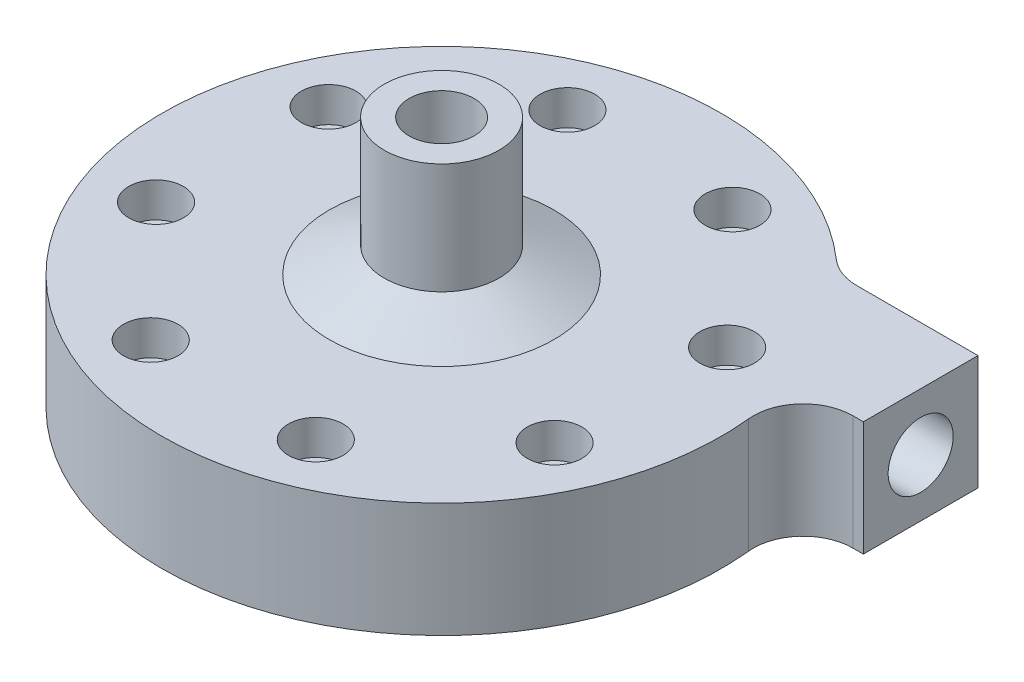
SolidWorks part; units mm, degrees
material "1060 Alloy"
ref_plane "Front" through (0, 0, 0) normal (0, 0, 1) x (1, 0, 0)
ref_plane "Top" through (0, 0, 0) normal (0, 1, 0) x (1, 0, 0)
ref_plane "Right" through (0, 0, 0) normal (1, 0, 0) x (0, 0, -1)
sketch "Sketch1" plane through (0, 0, 0) normal (0, 1, 0) x (1, 0, 0)
  line L0 (0, 0) -> (2.6731, 30.5538) construction
  line L1 (21.117, 30.6705) -> (50.1264, 33.2085) construction
  line L2 (11.6189, 28.3845) -> (50.1264, 28.3845) construction
  line L3 (21.117, 26.0945) -> (50.1264, 23.5565) construction
  line L4 (0, 0) -> (56.1418, -4.9118) construction
  line L5 (21.117, 30.6705) -> (21.117, 28.3845) construction
  line L6 (21.117, 28.3845) -> (21.117, 26.0945) construction
  line L7 (50.1264, 28.3845) -> (50.1264, 33.2085) construction
  line L8 (50.1264, 28.3845) -> (50.1264, 23.5565) construction
  line L9 (68.1264, 28.3845) -> (68.1264, 39.9329)
  line L10 (68.1264, 34.9329) -> (50.1264, 34.9329) construction
  line L11 (68.1264, 34.9329) -> (68.1264, 21.8361) construction
  line L12 (68.1264, 21.8361) -> (50.1264, 21.8361) construction
  line L13 (50.1264, 34.9329) -> (50.1264, 21.8361) construction
  line L14 (68.1264, 39.9329) -> (43.7019, 39.9329)
  line L15 (68.1264, 28.3845) -> (68.1264, 16.8361)
  line L16 (68.1264, 16.8361) -> (66.0032, 16.8361)
  line L17 (21.117, 30.6705) -> (0, 30.6705) construction
  line L18 (21.117, 26.0945) -> (16.117, 26.0945) construction
  arc A0 (37.1159, 42.408) -> (56.0564, 5.8059) centre (0, 0) ccw
  circle A1 centre (0, 0) radius 30.6705 construction
  arc A2 (66.0032, 16.8361) -> (56.0564, 5.8059) centre (66.0032, 6.8361) ccw
  arc A3 (43.7019, 39.9329) -> (37.1159, 42.408) centre (43.7019, 49.9329) cw
  dimension "D1" = 112.7125
  dimension "D2" = 61.341
  dimension "D13" = 10
  dimension "D4" = 2.286
  dimension "D3" = 2.29
  dimension "D5" = 5
  dimension "D6" = 5
  dimension "D7" = 5
  dimension "D8" = 9.652
  dimension "D9" = 13.0969
  dimension "D10" = 18
  dimension "D11" = 5
  dimension "D12" = 5
  dimension "D14" = 5
extrude "main body" add sketch "Sketch1" along normal blind 23.0969
ref_plane "body midsection" through (0, 11.5484, 0) normal (0, 1, 0) x (1, 0, 0)
sketch "Sketch7" plane through (0, 23.0969, 0) normal (0, 1, 0) x (1, 0, 0)
  circle A0 centre (0, 0) radius 25.4
  dimension "D1" = 50.8
extrude "inlet boss" add sketch "Sketch7" along normal blind 50.8
sketch "Sketch3" plane through (0, 11.5484, 0) normal (0, 1, 0) x (1, 0, 0)
  line L0 (21.117, 30.6705) -> (0, 30.6705)
  line L1 (0, 30.6705) -> (0, 28.3845)
  line L2 (50.1264, 28.3845) -> (2.4833, 28.3845)
  line L3 (0, 0) -> (2.6731, 30.5538) construction
  line L4 (0, 28.3845) -> (2.4833, 28.3845)
  line L5 (50.1264, 33.2085) -> (50.1264, 34.9329)
  line L6 (50.1264, 34.9329) -> (68.1264, 34.9329)
  line L7 (68.1264, 34.9329) -> (68.1264, 28.3845)
  line L8 (68.1264, 28.3845) -> (50.1264, 28.3845)
  line L9 (21.117, 30.6705) -> (50.1264, 33.2085)
revolve "expansion cone and outlet" cut sketch "Sketch3" angle 360 about L2
sketch "Sketch2" plane through (0, 0, 0) normal (0, 0, 1) x (1, 0, 0)
  line L0 (-56.3562, 11.5484) -> (56.3562, 11.5484) construction
  line L1 (-56.3562, 23.0969) -> (-56.3562, 0) construction
  line L2 (56.3562, 0) -> (56.3562, 23.0969) construction
  line L3 (0, 0) -> (0, 23.0969) construction
  line L4 (25.4, 23.0969) -> (-25.4, 23.0969) construction
  line L5 (0, 25.0381) -> (0, 13.3702)
  line L6 (0, 13.3702) -> (26.67, 13.3702) construction
  line L7 (5.461, 25.0381) -> (5.6723, 25.4913) construction
  line L8 (26.67, 15.1482) -> (5.461, 15.1482) construction
  line L9 (26.67, 13.3702) -> (26.67, 15.1482) construction
  line L10 (0, 25.5898) -> (0, 50.5898)
  line L11 (26.67, 15.1482) -> (5.461, 25.0381) construction
  line L12 (5.461, 25.0381) -> (0, 25.0381) construction
  line L13 (5.461, 25.0381) -> (5.461, 13.3702) construction
  line L14 (0, 13.3702) -> (0, 11.3702) construction
  line L15 (0, 11.3702) -> (26.67, 11.3702) construction
  line L16 (26.67, 11.3702) -> (26.67, 13.3702) construction
  line L17 (0, 13.3702) -> (0, 10.8702)
  line L18 (0, 11.3702) -> (0, 10.8702) construction
  line L19 (0, 10.8702) -> (26.67, 10.8702) construction
  line L20 (26.67, 10.8702) -> (26.67, 11.3702) construction
  line L21 (26.67, 10.8702) -> (30.6705, 10.8702) construction
  line L22 (30.6705, 10.8702) -> (30.6705, 13.2827)
  line L23 (26.67, 15.1482) -> (30.6705, 13.2827) construction
  line L24 (5.461, 25.0381) -> (5.461, 25.5898) construction
  line L25 (5.461, 25.5898) -> (0, 25.5898) construction
  line L26 (0, 25.5898) -> (0, 25.0381)
  line L27 (30.6705, 13.2827) -> (30.6705, 13.8344)
  line L28 (30.6705, 13.8344) -> (5.461, 25.5898)
  line L29 (0, 10.8702) -> (0, 0)
  line L30 (0, 0) -> (30.6705, 0)
  line L31 (-56.3562, 0) -> (56.3562, 0) construction
  line L32 (30.6705, 0) -> (30.6705, 10.8702)
  line L33 (30.6705, 13.8344) -> (0, 13.8344) construction
  line L34 (21.117, 13.8344) -> (0, 13.8344) construction
  line L35 (0, 50.5898) -> (6.5484, 50.5898) construction
  line L36 (6.5484, 50.5898) -> (6.5484, 35.5898)
  line L37 (6.5484, 35.5898) -> (5.461, 35.5898)
  line L38 (5.461, 35.5898) -> (5.461, 25.5898)
  line L39 (0, 50.5898) -> (0, 73.8969)
  line L40 (0, 73.8969) -> (25.4, 73.8969)
  line L41 (6.5484, 50.5898) -> (11.5484, 50.5898)
  line L42 (25.4, 73.8969) -> (-25.4, 73.8969) construction
  line L44 (11.5484, 50.5898) -> (11.5484, 28.2681)
  line L45 (11.5484, 28.2681) -> (22.6381, 23.0969)
  line L46 (25.4, 73.8969) -> (25.4, 23.0969)
  line L47 (25.4, 23.0969) -> (22.6381, 23.0969)
  dimension "D12" = 5
  dimension "D1" = 5.461
  dimension "D2" = 26.67
  dimension "D3" = 11.6679
  dimension "D4" = 1.778
  dimension "D5" = 2
  dimension "D6" = 4.0005
  dimension "D8" = 0.5
  dimension "D9" = 10
  dimension "D10" = 15
  dimension "D11" = 6.5484
  dimension "D13" = 5
revolve "main chamber" cut sketch "Sketch2" angle 360 about L5
sketch "Sketch5" plane through (0, 23.0969, 0) normal (0, 1, 0) x (1, 0, 0)
  line L1 (17.9206, 40.6775) -> (41.4351, 16.0915) construction
  line L3 (11.6189, 28.3845) -> (50.1264, 28.3845) construction
  circle A0 centre (0, 0) radius 44.45 construction
  circle A1 centre (41.4351, 16.0915) radius 2.9766
  circle A2 centre (0, 0) radius 44.45 construction
  circle A3 centre (40.6775, -17.9206) radius 2.9766
  circle A4 centre (0, 0) radius 44.45 construction
  circle A5 centre (16.0915, -41.4351) radius 2.9766
  circle A6 centre (0, 0) radius 44.45 construction
  circle A7 centre (-17.9206, -40.6775) radius 2.9766
  circle A8 centre (0, 0) radius 44.45 construction
  circle A9 centre (-41.4351, -16.0915) radius 2.9766
  circle A10 centre (0, 0) radius 44.45 construction
  circle A11 centre (-40.6775, 17.9206) radius 2.9766
  circle A12 centre (0, 0) radius 44.45 construction
  circle A13 centre (-16.0915, 41.4351) radius 2.9766
  circle A14 centre (0, 0) radius 44.45 construction
  circle A15 centre (17.9206, 40.6775) radius 2.9766
  point P5 (29.6778, 28.3845)
  point P30 (0, 0)
  dimension "D1" = 88.9
  dimension "D2" = 5.9531
  dimension "D4" = 8
sketch "Sketch6" plane through (0, 23.0969, 0) normal (0, 1, 0) x (1, 0, 0)
  circle A0 centre (41.4351, 16.0915) radius 5.5
  circle A1 centre (40.6775, -17.9206) radius 5.5
  circle A2 centre (16.0915, -41.4351) radius 5.5
  circle A3 centre (-17.9206, -40.6775) radius 5.5
  circle A4 centre (-41.4351, -16.0915) radius 5.5
  circle A5 centre (-40.6775, 17.9206) radius 5.5
  circle A6 centre (-16.0915, 41.4351) radius 5.5
  circle A7 centre (17.9206, 40.6775) radius 5.5
  point P19 (0, 0)
  dimension "D1" = 11
  dimension "D2" = 8
ref_plane "exit axial plane" through (0, 0, -28.3845) normal (0, 0, -1) x (-1, 0, 0)
extrude "bolt clearances" cut sketch "Sketch5" against normal through all
extrude "bolt head clearance" cut sketch "Sketch6" against normal blind 7
equation "\"bearing OD\" = 30mm"
equation "\"bearing ID\"= 10mm"
equation "\"bearing depth\"= 9mm"
equation "\"bearing outer race thickness\"= 1mm"
equation "\"bearing inner race thickness\"= 1mm"
equation "\"bearing bore\" = \"bearing depth\" + 1mm"
equation "\"z\" = 8 \t\t\t'number of blades"
equation "\"de\" = 0.43in\t\t\t'entrance eye diameter"
equation "\"d2\" = 2.1in \t\t\t'outer diameter of the impeller"
equation "\"d_exit\" = 0.18in \t\t'exit throat aka D4"
equation "\"theta\" = 25\t\t\t'angle of blades from inner to outer "
equation "\"b2\" = .07in\t\t\t\t\t\t\t'tip height from disc surface at d2"
equation "\"b1\" = \"b2\" + (\"d2\"/2 - \"de\"/2)*tan(\"theta\") \t\t\t'tip height from disc surface at inlet eye"
equation "\"s\"=\"ce\" - \"z\"*\"s_open\""
equation "\"impeller upper clearance\"= .5mm"
equation "\"impeller horizontal clearance\"= (\"d2\"*1.15 - \"d2\")/2 \t\t'clearance based on D2-D3 ratio for circular volute, ranges 1.15 to 1.2"
equation "\"impeller bottom clearance\"= .5mm"
equation "\"impeller base thickness\"= 2mm"
equation "\"impeller dowel diameter\" = 2mm"
equation "\"impeller bolt head diameter\" = \"m4 head bore diameter\""
equation "\"impeller bolt head depth\" = 4mm"
equation "\"impeller bolt stop depth\" = 3mm"
equation "\"impeller bolt bore\" = \"m4 clearance\""
equation "\"impeller shaft bore depth\" = 12mm"
equation "\"impeller shaft bore\" = 8mm"
equation "\"impeller boss depth\" = \"impeller shaft bore depth\"+\"impeller bolt stop depth\"+\"impeller bolt head depth\"-\"impeller base thickness\""
equation "\"impeller boss diameter\" = \"upper seal ID\""
equation "\"impeller dowel length\" = 2mm*2 + \"impeller shaft bore\""
equation "\"coupler motor shaft hole ID\"= 8mm"
equation "\"coupler OD\"= 17mm"
equation "\"coupler length\"= 25mm"
equation "\"motor OD\" = 64mm"
equation "\"motor shaft diameter\"= 8mm"
equation "\"motor shaft pride\"= 32mm"
equation "\"motor to bearing plate distance\" = \"motor shaft pride\" + 2mm +\"coupler length\"/2"
equation "\"square plate bolt bore\" = \"m8 clearance\""
equation "\"square plate bolt head diameter\" = 13.5mm"
equation "\"square plate bolt head depth\" = 8mm"
equation "\"square plate bolt pattern diameter\"= 3.5in"
equation "\"motor mount center bore\"= \"coupler OD\"+ 4mm"
equation "\"motor mount post radius\"= ( 3 * \"square plate bolt bore\" ) / 2"
equation "\"motor mount m4 screw hole diameter\"= 4mm"
equation "\"motor mount m4 head diameter\"= 7.25mm"
equation "\"motor mount m4 head depth\"= 4mm"
equation "\"motor mount m4 pattern diamater\" = 30mm"
equation "\"motor mount plate thickness\"= 8mm + \"motor mount m4 head depth\""
equation "\"bearing plate stop ID\" = \"bearing OD\" - 4mm"
equation "\"bearing plate stop depth\" = 3mm"
equation "\"bearing plate thickness\" = \"bearing bore\" + \"bearing plate stop depth\" + \"shaft bearing stop length\""
equation "\"shaft coupler section diameter\" = 8mm"
equation "\"shaft coupler section length\" = \"motor to bearing plate distance\" - \"motor shaft pride\" - 2mm"
equation "\"shaft bearing section diameter\" = \"bearing ID\""
equation "\"shaft bearing section length\" = \"bearing plate stop depth\" + \"bearing depth\""
equation "\"shaft bearing stop diameter\" = \"bearing ID\" + 4mm"
equation "\"shaft bearing stop length\" = 3mm"
equation "\"impeller cavity center height\"= \"impeller bottom clearance\" + \"impeller upper clearance\" + \"impeller center height\""
equation "\"impeller cavity diameter\"= 2 * \"impeller horizontal clearance\" + \"d2\" \t\t\t\t\t\t\t\t\t'called D3 analytically"
equation "\"impeller cavity outer height\"= \"impeller bottom clearance\" + \"impeller upper clearance\" + \"impeller base thickness\" + \"b2\" \t\t'this is height at impeller diameter d2, not at d3"
equation "\"impeller housing thickness\"= \"impeller housing exit threaded diameter\" + 2*\"impeller housing outlet grip\""
equation "\"impeller housing diameter\" = \"square plate bolt pattern diameter\" + 2*\"motor mount post radius\""
equation "\"impeller housing bolt count\" = 8"
equation "\"impeller housing bolt diameter\" = \"m6 clearance\""
equation "\"impeller housing bolt pattern diameter\" = 3.5in"
equation "\"impeller housing threaded inlet diameter\" = 0.515625in \t'this is the 33/64 drill size for 9/16-18 fitting, expecting swagelok SS-8FK0-1-6STH fitting"
equation "\"impeller housing threaded inlet depth\"= 15mm"
equation "\"impeller housing exit threaded diameter\"= 0.515625in \t\t'this is the 33/64 drill size for 9/16-18 fitting, expecting swagelok SS-8FK0-1-6STH fitting"
equation "\"impeller housing exit threaded depth\"= 18mm"
equation "\"impeller housing diffuser conical angle\"=10"
equation "\"impeller housing diffuser tangent angle\"=5"
equation "\"impeller housing diffuser final diameter\" = .38in"
equation "\"impeller housing outlet grip\" = 5mm"
equation "\"D1@Sketch1\"=\"impeller housing diameter\""
equation "\"D2@Sketch1\"=\"impeller cavity diameter\""
equation "\"D4@Sketch1\"=\"d_exit\"/2"
equation "\"D5@Sketch1\"=\"impeller housing diffuser tangent angle\""
equation "\"D6@Sketch1\"=\"impeller housing diffuser conical angle\"/2"
equation "\"D7@Sketch1\"=\"impeller housing diffuser conical angle\"/2"
equation "\"D8@Sketch1\"=\"impeller housing diffuser final diameter\""
equation "\"D9@Sketch1\"=\"impeller housing exit threaded diameter\""
equation "\"D10@Sketch1\"=\"impeller housing exit threaded depth\""
equation "\"D11@Sketch1\"=\"impeller housing outlet grip\""
equation "\"D12@Sketch1\"=\"impeller housing outlet grip\""
equation "\"D1@main body\" = \"impeller housing thickness\""
equation "\"de_length\" = 10mm\t\t'entrance eye consistent length"
equation "\"D1@Sketch5\"=\"impeller housing bolt pattern diameter\""
equation "\"D2@Sketch5\"=\"m6 clearance\""
equation "\"end mill size\" = 0.375in\t'for 3/8 endmill"
equation "\"ae\" = 3.14*(\"de\"^2)/4\t\t'entrance eye area'"
equation "\"ce\" = 3.14*\"de\"\t\t'entrance eye circumference"
equation "\"av_ratio\" = .325\t\t'ratio of av/ae at N_s of 470, range is .275 to .375, .325 ideal. High ratio means bigger area means smaller blades"
equation "\"av\" = \"ae\"*\"av_ratio\"\t\t'area between just two blades"
equation "\"s_open\" = \"av\"/\"b1\"\t\t'width of open area"
equation "\"impeller center height\" = \"impeller base thickness\" + \"b1\"\t'impeller height at de"
equation "\"impeller outer height\" = \"impeller base thickness\" + \"b2\"\t'impeller height at de"
equation "\"shaft impeller section diameter\" = \"impeller shaft bore\""
equation "\"shaft impeller section length\" = \"upper seal plate thickness\" + \"upper seal plate riser\" + \"impeller bottom clearance\" + \"impeller base thickness\" - \"impeller bolt head depth\" - \"impeller bolt stop depth\""
equation "\"m6 clearance\" = 0.234375in\t'this is 15/64 bit = 5.95mm, could use 6mm bit, B bit for 6.04mm or 1/4 bit for 6.35mm"
equation "\"m6 tap\" = 5mm\t\t\t'5mm is appropriate, could use 13/64 or #5,6,7"
equation "\"m6 head bore diameter\" = 11mm\t\t"
equation "\"m6 head bore depth\" = 7mm\t'actual is 6mm"
equation "\"m8 clearance\" = 0.3125in\t'this is 5/16in for 7.93mm, could use 8mm, O,P, or 21/64"
equation "\"m8 tap\" = 0.265625in\t\t'this is 17/64 for 6.746875mm"
equation "\"m8 head bore diameter\" = 14mm"
equation "\"m8 head bore depth\" = 9mm\t'actual is 8mm"
equation "\"D1@Sketch6\"=\"m6 head bore diameter\""
equation "\"D1@bolt head clearance\" = \"m6 head bore depth\""
equation "\"lower seal OD\" = .917in\t\t'this is https://www.mcmaster.com/#9281k121/=174001b"
equation "\"lower seal ID\"= .375in"
equation "\"lower seal depth\" = .625in + .218in"
equation "\"lower seal bore\" = \"lower seal depth\" + 1mm"
equation "\"upper seal OD\" = 1.125in\t'this is https://www.mcmaster.com/#5154t33/=173zuau, needs to be visually inspected before machining!"
equation "\"upper seal ID\"= 0.625in"
equation "\"upper seal depth\"= .25in\t'aka height; these values need to be confirmed by inspection!! We may want to compress the height."
equation "\"upper seal bore\" = \"upper seal depth\" + 1mm"
equation "\"big o-ring thickness\" = .139in"
equation "\"big o-ring OD\" = 2.734in"
equation "\"big o-ring ID\" = 3.012in"
equation "\"big o-ring groove depth\" = \"big o-ring thickness\"*4/5"
equation "\"lower seal plate lip depth\" = 2mm"
equation "\"lower seal plate lip ID\" = \"lower seal OD\" - 3mm"
equation "\"lower seal plate thickness\" = \"lower seal plate lip depth\" + \"lower seal bore\""
equation "\"shaft lower seal section diameter\" = \"lower seal ID\""
equation "\"shaft lower seal section length\" = \"lower seal plate thickness\" + 1mm"
equation "\"upper seal plate thickness\" = \"upper seal plate pressure hole diameter\"*3"
equation "\"upper seal plate lip ID\" = \"upper seal OD\" - 3mm"
equation "\"upper seal plate riser\" = \"impeller housing thickness\"/2 - \"b2\"/2 - \"impeller base thickness\" - \t\"impeller bottom clearance\"\t\t\t'this offsets the gap under the housing"
equation "\"upper seal plate pressure hole diameter\" = .125in\t'this is 1/8 drill "
equation "\"upper seal plate pressure tap diameter\" = .328125in \t'this is 21/64 drill for a 1/8 ANPT tap"
equation "\"upper seal plate pressure tap grip\" = 4mm\t\t'this is the area around the tap so it doesn't crack"
equation "\"upper seal plate pressure tap depth\" = 12"
equation "\"m4 clearance\" = 0.171875in \t'this is 11/64 bit for 4.36mm"
equation "\"m4 tap\" = 0.125in\t\t'this is 1/8 bit for 3.17mm"
equation "\"m4 head bore diameter\" = 7.5mm"
equation "\"m4 head bore depth\" = 5mm\t'actual is ~4mm"
equation "\"l_exit\" = 5mm\t\t\t'exit throad length"
equation "\"D1@Sketch2\"=\"de\"/2"
equation "\"D3@Sketch2\"=\"b1\""
equation "\"D4@Sketch2\"=\"b2\""
equation "\"D2@Sketch2\"=\"d2\"/2"
equation "\"D5@Sketch2\"=\"impeller base thickness\""
equation "\"D6@Sketch2\"=\"impeller horizontal clearance\""
equation "\"D7@Sketch2\"=\"impeller bottom clearance\""
equation "\"D8@Sketch2\"=\"impeller upper clearance\""
equation "\"D9@Sketch2\"=\"de_length\""
equation "\"D10@Sketch2\"=\"impeller housing threaded inlet depth\""
equation "\"D11@Sketch2\"=\"impeller housing threaded inlet diameter\"/2"
equation "\"D12@Sketch2\"=\"impeller housing outlet grip\""
equation "\"D13@Sketch2\"=\"impeller housing outlet grip\""
